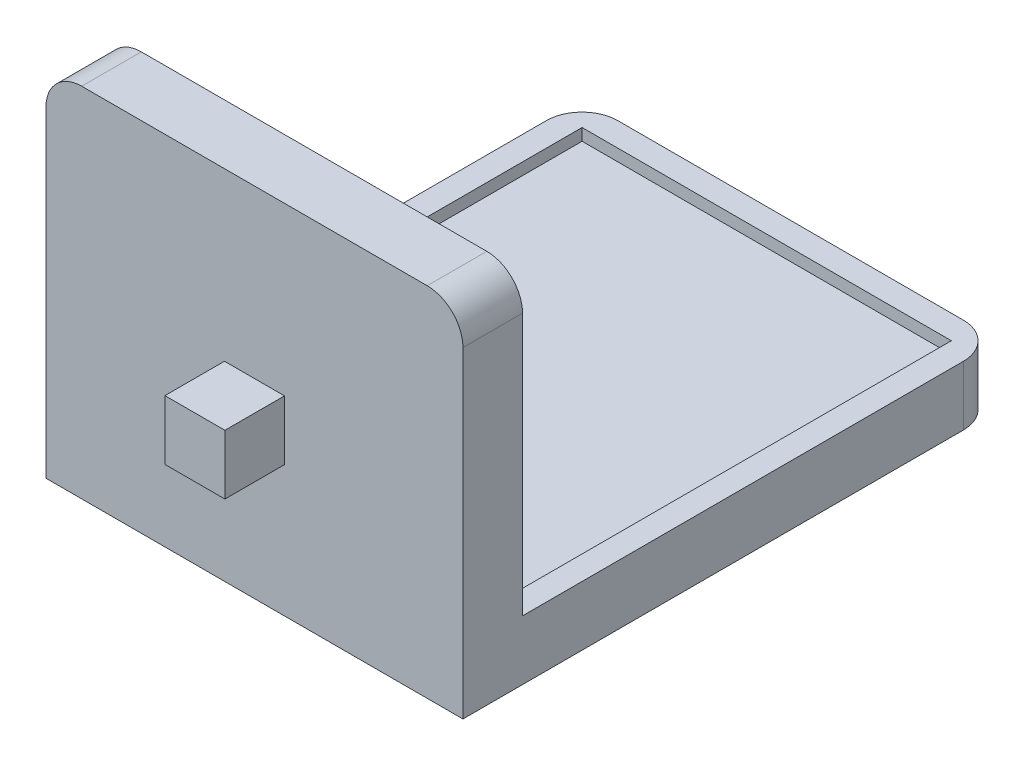
SolidWorks part; units mm, degrees
ref_plane "Front Plane" through (0, 0, 0) normal (0, 0, 1) x (1, 0, 0)
ref_plane "Top Plane" through (0, 0, 0) normal (0, 1, 0) x (1, 0, 0)
ref_plane "Right Plane" through (0, 0, 0) normal (1, 0, 0) x (0, 0, -1)
sketch "Sketch1" plane through (0, 0, 0) normal (0, 1, 0) x (1, 0, 0)
  line L1 (0, 0) -> (35, 0)
  line L2 (0, 0) -> (0, 40)
  line L3 (0, 40) -> (35, 40)
  line L4 (35, 0) -> (35, 40)
extrude "Boss-Extrude1" add sketch "Sketch1" along normal blind 5
sketch "Sketch2" plane through (0, 5, 0) normal (0, 1, 0) x (1, 0, 0)
  line L24 (2, 2) -> (33, 2)
  line L25 (33, 2) -> (33, 38)
  line L26 (2, 38) -> (2, 2)
  line L27 (33, 38) -> (2, 38)
extrude "Cut-Extrude1" cut sketch "Sketch2" against normal blind 1
sketch "Sketch3" plane through (0, 0, 0) normal (0, 0, 1) x (1, 0, 0)
  line L1 (0, 0) -> (35, 0)
  line L2 (0, 0) -> (0, 30)
  line L3 (0, 30) -> (35, 30)
  line L4 (35, 0) -> (35, 30)
extrude "Boss-Extrude2" add sketch "Sketch3" along normal blind 5
fillet "Fillet2" radius 3 1 edges at (0, 2.5, -40)
fillet "Fillet3" radius 3 1 edges at (35, 2.5, -40)
fillet "Fillet4" radius 3 2 edges at (35, 30, 2.5) (0, 30, 2.5)
sketch "Sketch4" plane through (0, 0, 5) normal (0, 0, 1) x (1, 0, 0)
  line L6 (14.9819, 11) -> (20.0181, 11)
  line L7 (14.9819, 11) -> (14.9819, 16)
  line L8 (14.9819, 16) -> (20.0181, 16)
  line L9 (20.0181, 11) -> (20.0181, 16)
  line L10 (14.9819, 11) -> (20.0181, 16) construction
  line L11 (14.9819, 16) -> (20.0181, 11) construction
extrude "Boss-Extrude3" add sketch "Sketch4" along normal blind 5
